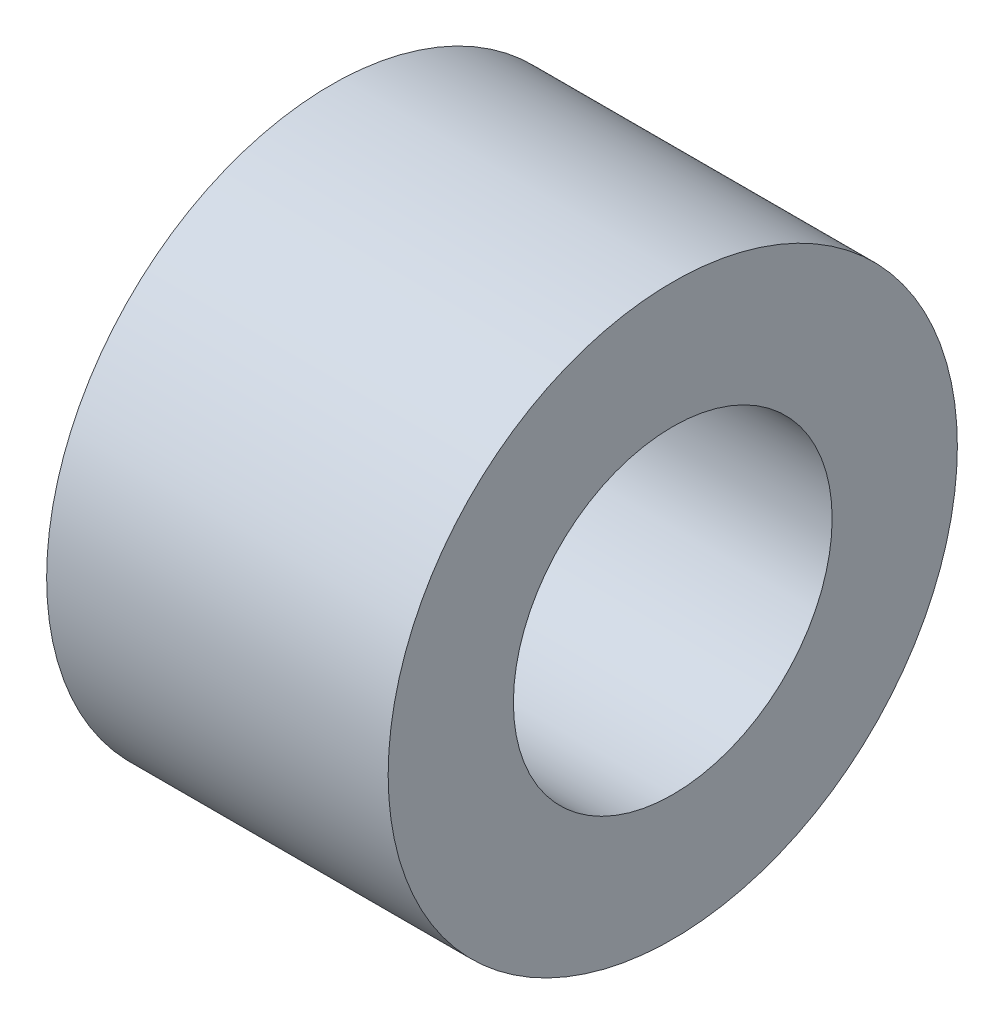
SolidWorks part; units mm, degrees
ref_plane "Front Plane" through (0, 0, 0) normal (1, 0, 0) x (0, 1, 0)
ref_plane "Top Plane" through (0, 0, 0) normal (0, 0, 1) x (0, 1, 0)
ref_plane "Right Plane" through (0, 0, 0) normal (0, 1, 0) x (-1, 0, 0)
sketch "Sketch1" plane through (0, 0, 0) normal (1, 0, 0) x (0, 1, 0)
  circle A0 centre (0, 0) radius 1.4
  circle A1 centre (0, 0) radius 2.5
  dimension "D1" = 2.8
  dimension "D2" = 5
extrude "Boss-Extrude1" add sketch "Sketch1" along normal blind 3 contours A1 | A0
